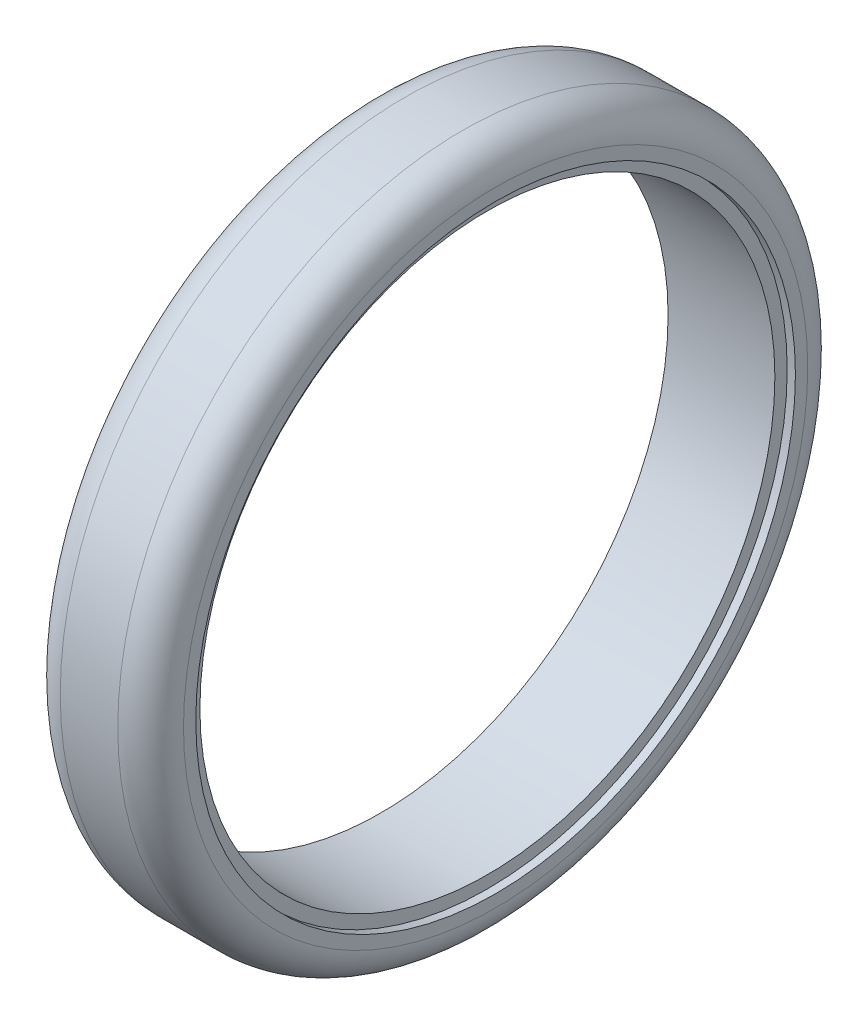
SolidWorks part; units mm, degrees
material "Rubber"
ref_plane "Front Plane" through (0, 0, 0) normal (0, 0, 1) x (1, 0, 0)
ref_plane "Top Plane" through (0, 0, 0) normal (0, 1, 0) x (1, 0, 0)
ref_plane "Right Plane" through (0, 0, 0) normal (1, 0, 0) x (0, 0, -1)
sketch "Sketch1" plane through (0, 0, 0) normal (0, 0, 1) x (1, 0, 0)
  line L0 (0, 0) -> (0, 35)
  line L1 (-6.5, 35) -> (6.5, 35)
  line L2 (-6.5, 35) -> (-6.5, 36.5)
  line L3 (-6.5, 36.5) -> (-7.5, 36.5)
  line L4 (-7.5, 36.5) -> (-7.5, 38)
  line L5 (6.5, 35) -> (6.5, 36.5)
  line L6 (6.5, 36.5) -> (7.5, 36.5)
  line L7 (7.5, 36.5) -> (7.5, 38)
  line L8 (-3.5, 42) -> (3.5, 42)
  line L9 (-2.5422, 42) -> (2.4578, 42)
  line L10 (-3.2922, 42) -> (-1.7922, 42)
  line L11 (-3.2922, 43) -> (-1.7922, 43)
  line L12 (-3.2922, 43) -> (-3.2922, 41)
  line L13 (-3.2922, 41) -> (-1.7922, 41)
  line L14 (-1.7922, 43) -> (-1.7922, 41)
  line L15 (-3.2922, 43) -> (-1.7922, 41) construction
  line L16 (-3.2922, 41) -> (-1.7922, 43) construction
  line L17 (1.7078, 43) -> (3.2078, 43)
  line L18 (1.7078, 43) -> (1.7078, 41)
  line L19 (1.7078, 41) -> (3.2078, 41)
  line L20 (3.2078, 43) -> (3.2078, 41)
  line L21 (1.7078, 43) -> (3.2078, 41) construction
  line L22 (1.7078, 41) -> (3.2078, 43) construction
  line L23 (3.2078, 42) -> (1.7078, 42)
  arc A0 (7.5, 38) -> (3.5, 42) centre (3.5, 38) ccw
  arc A1 (-3.5, 42) -> (-7.5, 38) centre (-3.5, 38) ccw
  point P6 (0, 35)
  point P14 (7.5, 42)
  point P17 (-7.5, 42)
  point P21 (-0.0422, 42)
  dimension "D6" = 4
  dimension "D1" = 35
  dimension "D2" = 13
  dimension "D3" = 1.5
  dimension "D4" = 5.5
  dimension "D5" = 1
  dimension "D7" = 5
  dimension "D8" = 1.5
  dimension "D9" = 1.5
  dimension "D10" = 2
  dimension "2" = 2
sketch "Sketch2" plane through (0, 0, 0) normal (0, 1, 0) x (1, 0, 0)
  line L0 (-13.4108, 0) -> (13.3247, 0) construction
revolve "Revolve1" add sketch "Sketch1" angle 360 about L0
fillet "Fillet7" [suppressed] radius 1
fillet "Fillet8" [suppressed] radius 1
fillet "Fillet9" [suppressed] radius 1
ref_plane "Plane1" through (7.5, 0, 0) normal (1, 0, 0) x (0, 0, -1)
sketch "Sketch5" plane through (7.5, 0, 0) normal (1, 0, 0) x (0, 0, -1)
  line L0 (0, 0) -> (0, 41.5)
  line L1 (0, 41) -> (0, 42.3554)
  line L2 (2.5, 40.9237) -> (2.5, 42.2816)
  line L3 (13.9283, 38.5617) -> (14.3108, 39.8645)
  line L4 (11.551, 39.3392) -> (11.9329, 40.6397)
  line L5 (24.2282, 33.0756) -> (24.9623, 34.2179)
  line L6 (22.1663, 34.4914) -> (22.8991, 35.6317)
  line L7 (32.5652, 24.91) -> (33.5914, 25.7992)
  line L8 (30.9857, 26.8493) -> (32.0101, 27.7369)
  line L9 (38.2641, 14.7262) -> (39.4992, 15.2903)
  line L10 (37.2949, 17.032) -> (38.5278, 17.5951)
  line L11 (40.863, 3.3495) -> (42.207, 3.5427)
  line L12 (40.5827, 5.8349) -> (41.9243, 6.0278)
  line L13 (40.1514, -8.2986) -> (41.4954, -8.4918)
  line L14 (40.5827, -5.8349) -> (41.9243, -6.0278)
  line L15 (36.187, -19.2744) -> (37.4221, -19.8385)
  line L16 (37.2949, -17.032) -> (38.5278, -17.5951)
  line L17 (29.2909, -28.6887) -> (30.3171, -29.5779)
  line L18 (30.9857, -26.8493) -> (32.0101, -27.7369)
  line L19 (20.0219, -35.7788) -> (20.756, -36.9211)
  line L20 (22.1663, -34.4914) -> (22.8991, -35.6317)
  line L21 (9.1308, -39.9703) -> (9.5134, -41.2732)
  line L22 (11.551, -39.3392) -> (11.9329, -40.6397)
  line L23 (-2.5, -40.9237) -> (-2.5, -42.2816)
  line L24 (0, -41) -> (0, -42.3554)
  line L25 (-13.9283, -38.5617) -> (-14.3108, -39.8645)
  line L26 (-11.551, -39.3392) -> (-11.9329, -40.6397)
  line L27 (-24.2282, -33.0756) -> (-24.9623, -34.2179)
  line L28 (-22.1663, -34.4914) -> (-22.8991, -35.6317)
  line L29 (-32.5652, -24.91) -> (-33.5914, -25.7992)
  line L30 (-30.9857, -26.8493) -> (-32.0101, -27.7369)
  line L31 (-38.2641, -14.7262) -> (-39.4992, -15.2903)
  line L32 (-37.2949, -17.032) -> (-38.5278, -17.5951)
  line L33 (-40.863, -3.3495) -> (-42.207, -3.5427)
  line L34 (-40.5827, -5.8349) -> (-41.9243, -6.0278)
  line L35 (-40.1514, 8.2986) -> (-41.4954, 8.4918)
  line L36 (-40.5827, 5.8349) -> (-41.9243, 6.0278)
  line L37 (-36.187, 19.2744) -> (-37.4221, 19.8385)
  line L38 (-37.2949, 17.032) -> (-38.5278, 17.5951)
  line L39 (-29.2909, 28.6887) -> (-30.3171, 29.5779)
  line L40 (-30.9857, 26.8493) -> (-32.0101, 27.7369)
  line L41 (-20.0219, 35.7788) -> (-20.756, 36.9211)
  line L42 (-22.1663, 34.4914) -> (-22.8991, 35.6317)
  line L43 (-9.1308, 39.9703) -> (-9.5134, 41.2732)
  line L44 (-11.551, 39.3392) -> (-11.9329, 40.6397)
  arc A0 (0, 41) -> (2.5, 40.9237) centre (0, 0) cw
  arc A1 (0, 42.3554) -> (2.5, 42.2816) centre (0, 0) cw
  arc A2 (11.9329, 40.6397) -> (14.3108, 39.8645) centre (0, 0) cw
  arc A3 (11.551, 39.3392) -> (13.9283, 38.5617) centre (0, 0) cw
  arc A4 (22.8991, 35.6317) -> (24.9623, 34.2179) centre (0, 0) cw
  arc A5 (22.1663, 34.4914) -> (24.2282, 33.0756) centre (0, 0) cw
  arc A6 (32.0101, 27.7369) -> (33.5914, 25.7992) centre (0, 0) cw
  arc A7 (30.9857, 26.8493) -> (32.5652, 24.91) centre (0, 0) cw
  arc A8 (38.5278, 17.5951) -> (39.4992, 15.2903) centre (0, 0) cw
  arc A9 (37.2949, 17.032) -> (38.2641, 14.7262) centre (0, 0) cw
  arc A10 (41.9243, 6.0278) -> (42.207, 3.5427) centre (0, 0) cw
  arc A11 (40.5827, 5.8349) -> (40.863, 3.3495) centre (0, 0) cw
  arc A12 (41.9243, -6.0278) -> (41.4954, -8.4918) centre (0, 0) cw
  arc A13 (40.5827, -5.8349) -> (40.1514, -8.2986) centre (0, 0) cw
  arc A14 (38.5278, -17.5951) -> (37.4221, -19.8385) centre (0, 0) cw
  arc A15 (37.2949, -17.032) -> (36.187, -19.2744) centre (0, 0) cw
  arc A16 (32.0101, -27.7369) -> (30.3171, -29.5779) centre (0, 0) cw
  arc A17 (30.9857, -26.8493) -> (29.2909, -28.6887) centre (0, 0) cw
  arc A18 (22.8991, -35.6317) -> (20.756, -36.9211) centre (0, 0) cw
  arc A19 (22.1663, -34.4914) -> (20.0219, -35.7788) centre (0, 0) cw
  arc A20 (11.9329, -40.6397) -> (9.5134, -41.2732) centre (0, 0) cw
  arc A21 (11.551, -39.3392) -> (9.1308, -39.9703) centre (0, 0) cw
  arc A22 (0, -42.3554) -> (-2.5, -42.2816) centre (0, 0) cw
  arc A23 (0, -41) -> (-2.5, -40.9237) centre (0, 0) cw
  arc A24 (-11.9329, -40.6397) -> (-14.3108, -39.8645) centre (0, 0) cw
  arc A25 (-11.551, -39.3392) -> (-13.9283, -38.5617) centre (0, 0) cw
  arc A26 (-22.8991, -35.6317) -> (-24.9623, -34.2179) centre (0, 0) cw
  arc A27 (-22.1663, -34.4914) -> (-24.2282, -33.0756) centre (0, 0) cw
  arc A28 (-32.0101, -27.7369) -> (-33.5914, -25.7992) centre (0, 0) cw
  arc A29 (-30.9857, -26.8493) -> (-32.5652, -24.91) centre (0, 0) cw
  arc A30 (-38.5278, -17.5951) -> (-39.4992, -15.2903) centre (0, 0) cw
  arc A31 (-37.2949, -17.032) -> (-38.2641, -14.7262) centre (0, 0) cw
  arc A32 (-41.9243, -6.0278) -> (-42.207, -3.5427) centre (0, 0) cw
  arc A33 (-40.5827, -5.8349) -> (-40.863, -3.3495) centre (0, 0) cw
  arc A34 (-41.9243, 6.0278) -> (-41.4954, 8.4918) centre (0, 0) cw
  arc A35 (-40.5827, 5.8349) -> (-40.1514, 8.2986) centre (0, 0) cw
  arc A36 (-38.5278, 17.5951) -> (-37.4221, 19.8385) centre (0, 0) cw
  arc A37 (-37.2949, 17.032) -> (-36.187, 19.2744) centre (0, 0) cw
  arc A38 (-32.0101, 27.7369) -> (-30.3171, 29.5779) centre (0, 0) cw
  arc A39 (-30.9857, 26.8493) -> (-29.2909, 28.6887) centre (0, 0) cw
  arc A40 (-22.8991, 35.6317) -> (-20.756, 36.9211) centre (0, 0) cw
  arc A41 (-22.1663, 34.4914) -> (-20.0219, 35.7788) centre (0, 0) cw
  arc A42 (-11.9329, 40.6397) -> (-9.5134, 41.2732) centre (0, 0) cw
  arc A43 (-11.551, 39.3392) -> (-9.1308, 39.9703) centre (0, 0) cw
  dimension "D3" = 2.5
  dimension "D1" = 41.5
  dimension "D2" = 41
  dimension "D4" = 22
extrude "Cut-Extrude2" [suppressed] cut sketch "Sketch5" against normal through all contours A1 L1 L0 A0 L2 | L42 A40 L41 A41 | A43 L43 A42 L44 | A2 L3 A3 L4 | A4 L5 A5 L6 | A7 L7 A6 L8 | A8 L9 A9 L10 | A11 L11 A10 L12 | A12 L13 A13 L14 | A14 L15 A15 L16 | A16 L17 A17 L18 | A18 L19 A19 L20 | A21 L21 A20 L22 | A22 L23 A23 L24 | A24 L25 A25 L26 | A26 L27 A27 L28 | L30 A28 L29 A29 | A30 L31 A31 L32 | A33 L33 A32 L34 | A34 L35 A35 L36 | A36 L37 A37 L38 | A39 L39 A38 L40
